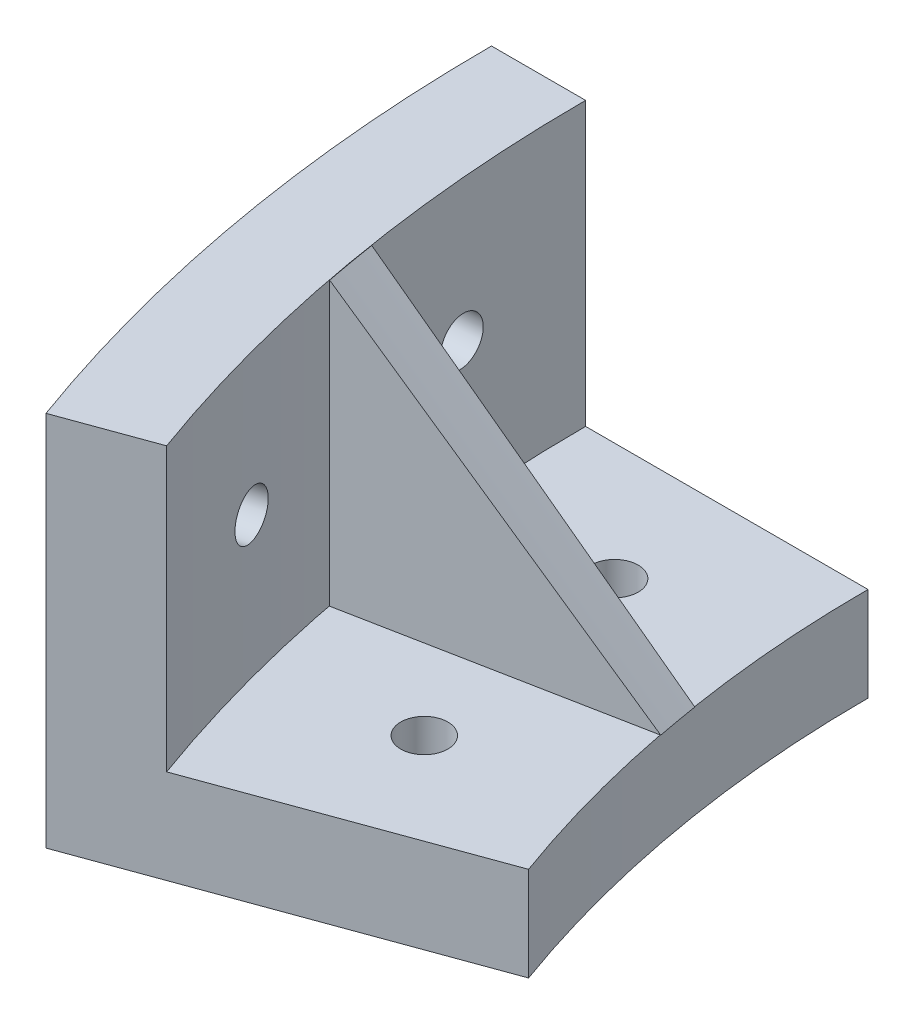
SolidWorks part; units mm, degrees
ref_plane "Plan de face" through (0, 0, 0) normal (0, 0, 1) x (1, 0, 0)
ref_plane "Plan de dessus" through (0, 0, 0) normal (0, 1, 0) x (1, 0, 0)
ref_plane "Plan de droite" through (0, 0, 0) normal (1, 0, 0) x (0, 0, -1)
sketch "Esquisse2" plane through (0, 0, 0) normal (0, 0, 1) x (1, 0, 0)
  line L0 (0, 0) -> (20, 0)
  line L1 (20, 0) -> (20, 5)
  line L2 (20, 5) -> (5, 5)
  line L3 (5, 5) -> (5, 20)
  line L4 (5, 20) -> (0, 20)
  line L5 (0, 20) -> (0, 0)
  line L6 (84, 0) -> (84, 20) construction
  dimension "D1" = 20
  dimension "D2" = 20
  dimension "D3" = 5
  dimension "D4" = 5
  dimension "D5" = 84
revolve "Révolution1" add sketch "Esquisse2" angle 20 about L6
sketch "Esquisse4" plane through (0, 5, 0) normal (0, 1, 0) x (1, 0, 0)
  line L0 (20, 0) -> (5, 0) construction
  line L1 (12.7721, -6.2316) -> (84, 0) construction
  line L2 (84, 0) -> (12.5, 0) construction
  line L3 (14.9363, -18.5056) -> (84, 0) construction
  circle A0 centre (84, 0) radius 71.5 construction
  circle A1 centre (14.9363, -18.5056) radius 1.25
  circle A2 centre (12.7721, -6.2316) radius 1.25
  point P11 (88.3751, 0.7715)
  dimension "D1" = 5
  dimension "D3" = 143
  dimension "D4" = 10
  dimension "D2" = 2
extrude "Enlèv. mat.-Extru.1" cut sketch "Esquisse4" against normal blind 10
ref_plane "Plan1" through (-0.3184, 0, 0.0279) normal (-0.9962, 0, 0.0872) x (0, -1, 0)
sketch "Esquisse6" plane through (0, 0, 0) normal (0, 1, 0) x (1, 0, 0)
  line L0 (84, 0) -> (0.3196, -7.3211) construction
  line L1 (84, 0) -> (0, 0) construction
  arc A0 (0, 0) -> (5.0658, -28.7297) centre (84, 0) ccw construction
  point P7 (0.3196, -7.3211)
  dimension "D1" = 5
sketch "Esquisse7" plane through (-0.3184, 0, 0.0279) normal (-0.9962, 0, 0.0872) x (0, -1, 0)
  line L0 (-20, 7.3211) -> (0, 7.3211) construction
  circle A0 centre (-12.5, 7.3211) radius 1.25
  dimension "D1" = 12.5
extrude "Enlèv. mat.-Extru.2" cut sketch "Esquisse7" against normal blind 10
pattern_circular "Répétition circulaire1" count 2 every 10 about axis through (84, 0, 0) along (0, -1, 0) of "Enlèv. mat.-Extru.2"
ref_plane "Plan2" through (2.5329, 0, 14.3648) normal (-0.1736, 0, -0.9848) x (-0.9848, 0, 0.1736)
sketch "Esquisse9" plane through (2.5329, 0, 14.3648) normal (-0.1736, 0, -0.9848) x (-0.9848, 0, 0.1736)
  line L0 (-3.7466, 5) -> (-3.7466, 20)
  line L1 (-3.7239, 5) -> (-4.924, 5) construction
  line L2 (-3.7239, 20) -> (-4.924, 20) construction
  line L3 (-4.924, 20) -> (0, 20) construction
  line L4 (-3.7466, 20) -> (-18.7466, 5)
  line L5 (-19.6962, 5) -> (-4.924, 5) construction
  line L6 (-18.7466, 5) -> (-3.7466, 5)
revolve "Révolution2" add sketch "Esquisse9" angle 1 about axis through (84, 0, 0) along (0, -1, 0) other way angle 1
